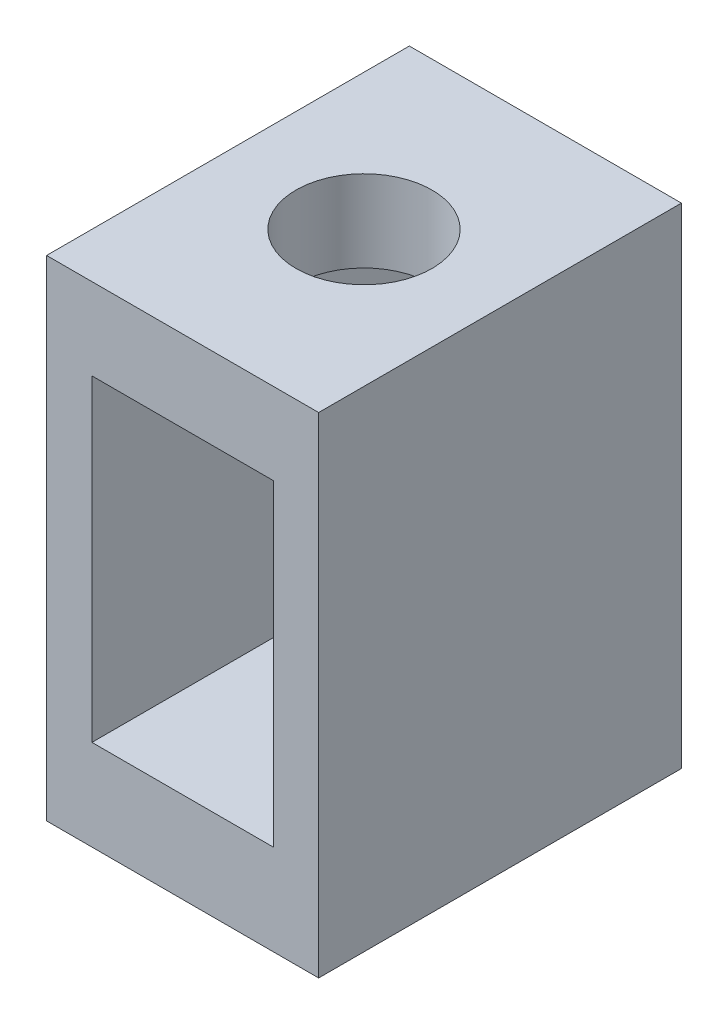
SolidWorks part; units mm, degrees
ref_plane "Спереди" through (0, 0, 0) normal (0, 0, 1) x (1, 0, 0)
ref_plane "Сверху" through (0, 0, 0) normal (0, 1, 0) x (1, 0, 0)
ref_plane "Справа" through (0, 0, 0) normal (1, 0, 0) x (0, 0, -1)
sketch "Эскиз1" plane through (0, 0, 0) normal (0, 0, 1) x (1, 0, 0)
  line L1 (-1.5, 2.7) -> (1.5, 2.7)
  line L2 (-1.5, 2.7) -> (-1.5, -2.7)
  line L3 (-1.5, -2.7) -> (1.5, -2.7)
  line L4 (1.5, 2.7) -> (1.5, -2.7)
  line L5 (-1.5, 2.7) -> (1.5, -2.7) construction
  line L6 (-1.5, -2.7) -> (1.5, 2.7) construction
  point P0 (0, 0)
  dimension "D1" = 3
  dimension "D2" = 5.4
extrude "Бобышка-Вытянуть1" add sketch "Эскиз1" against normal blind 4
sketch "Эскиз2" plane through (0, 0, 0) normal (0, 0, 1) x (1, 0, 0)
  line L0 (-1.5, -2.7) -> (1.5, -2.7) construction
  line L1 (-1, 1.8) -> (1, 1.8)
  line L2 (-1, 1.8) -> (-1, -1.7)
  line L3 (-1, -1.7) -> (1, -1.7)
  line L4 (1, 1.8) -> (1, -1.7)
  line L5 (-1, 1.8) -> (1, -1.7) construction
  line L6 (0, 2.7) -> (0, -2.7) construction
  line L7 (1.5, 2.7) -> (-1.5, 2.7) construction
  point P10 (0, 0.05)
  dimension "D1" = 3.5
  dimension "D2" = 1
  dimension "D3" = 2
extrude "Вырез-Вытянуть1" cut sketch "Эскиз2" against normal through all
sketch "Эскиз3" plane through (0, 2.7, 0) normal (0, 1, 0) x (1, 0, 0)
  line L0 (-1.5, 4) -> (1.5, 0) construction
  circle A0 centre (0, 2) radius 0.75
  dimension "D1" = 1.5
extrude "Вырез-Вытянуть2" cut sketch "Эскиз3" against normal up to next
